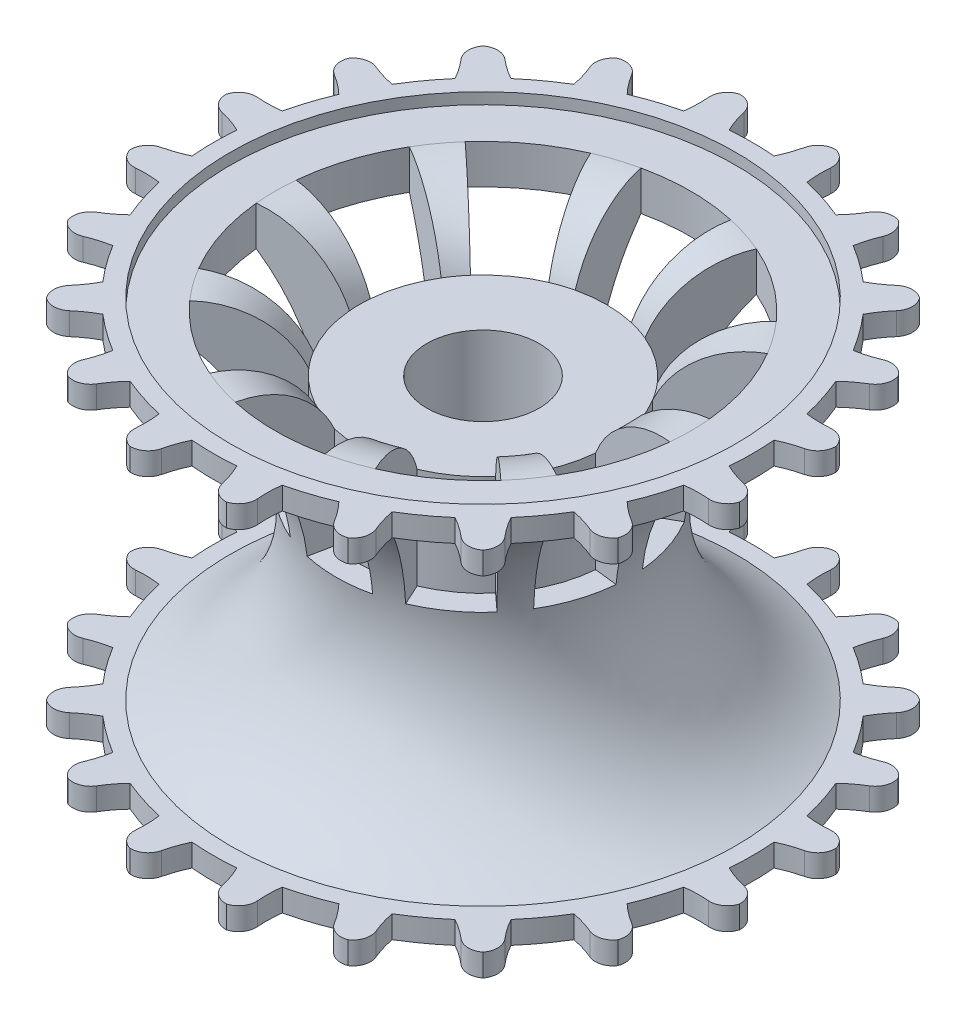
SolidWorks part; units mm, degrees
material "PE(聚乙烯)"
ref_plane "前视" through (0, 0, 0) normal (0, 0, 1) x (1, 0, 0)
ref_plane "上视" through (0, 0, 0) normal (0, 1, 0) x (1, 0, 0)
ref_plane "右视" through (0, 0, 0) normal (1, 0, 0) x (0, 0, -1)
sketch "草图1" plane through (0, 0, 0) normal (0, 0, 1) x (1, 0, 0)
  line L0 (0, 0) -> (0, -60) construction
  line L1 (5, 0) -> (11, 0)
  line L2 (22.5, 6) -> (27.5, 6)
  line L3 (27.5, 6) -> (27.5, 4)
  line L4 (27.5, 4) -> (22.5, 4)
  line L5 (5, 0) -> (5, -14)
  line L6 (5, -14) -> (2, -14)
  line L7 (2, -14) -> (2, -19)
  line L8 (22.5, 6) -> (22.5, 5)
  line L9 (22.5, 5) -> (18.5, 5)
  line L10 (22.5, -25) -> (27.5, -25)
  line L11 (27.5, -25) -> (27.5, -27)
  line L12 (27.5, -27) -> (22.5, -27)
  line L13 (12.5, -17) -> (10, -17)
  line L14 (10, -17) -> (10, -19)
  line L15 (10, -19) -> (6, -19)
  line L16 (6, -19) -> (6, -27)
  line L17 (6, -27) -> (4, -27)
  line L18 (2, -19) -> (4, -19)
  line L19 (4, -19) -> (4, -27)
  arc A0 (11, 0) -> (18.5, 5) centre (18.5, -3.125) cw
  arc A1 (22.5, 4) -> (22.5, -25) centre (28.8158, -10.5) ccw
  arc A2 (22.5, -27) -> (12.5, -17) centre (27.4359, -12.0641) cw
  dimension "D14" = 26
  dimension "D1" = 60
  dimension "D2" = 10
  dimension "D3" = 14
  dimension "D4" = 4
  dimension "D5" = 55
  dimension "D6" = 22
  dimension "D7" = 6
  dimension "D8" = 1
  dimension "D9" = 5
  dimension "D10" = 2
  dimension "D11" = 4
  dimension "D12" = 33
  dimension "D13" = 2
  dimension "D15" = 5
  dimension "D16" = 5
  dimension "D17" = 25
  dimension "D18" = 20
  dimension "D19" = 12
  dimension "D20" = 8
  dimension "D21" = 5
  dimension "D22" = 10
  dimension "D23" = 8
  dimension "D24" = 5
revolve "旋转1" add sketch "草图1" angle 360 about L0
sketch "草图2" plane through (0, 6, 0) normal (0, 1, 0) x (1, 0, 0)
  line L0 (-4, 18.0624) -> (-2.5, 10.7121)
  line L1 (0, 27.5) -> (0, -27.5) construction
  line L2 (2.5, 10.7121) -> (4, 18.0624)
  circle A0 centre (0, 0) radius 18.5 construction
  arc A1 (4, 18.0624) -> (-4, 18.0624) centre (0, 0) ccw
  circle A2 centre (0, 0) radius 11 construction
  arc A3 (2.5, 10.7121) -> (-2.5, 10.7121) centre (0, 0) ccw
  circle A4 centre (0, 0) radius 27.5 construction
  dimension "D1" = 8
  dimension "D2" = 5
extrude "切除-拉伸1" cut sketch "草图2" against normal blind 15
pattern_circular "阵列(圆周)1" count 10 over 360 about axis through (0, 0, 0) along (0, 1, 0) of "切除-拉伸1"
sketch "草图3" plane through (0, 6, 0) normal (0, 1, 0) x (1, 0, 0)
  line L0 (0, 27.5) -> (0, -27.5) construction
  arc A0 (2, 23.9165) -> (-2, 23.9165) centre (0, 0) ccw
  arc A1 (-2.708, 25.9327) -> (-2, 23.9165) centre (6.8709, 28.1642) ccw
  circle A2 centre (0, 0) radius 27.5 construction
  arc A3 (2.708, 25.9327) -> (2, 23.9165) centre (-6.8709, 28.1642) cw
  arc A4 (4.5, 27.1293) -> (-4.5, 27.1293) centre (0, 0) ccw
  arc A5 (-2.708, 25.9327) -> (-4.5, 27.1293) centre (-4.2422, 25.5753) ccw
  arc A6 (2.708, 25.9327) -> (4.5, 27.1293) centre (4.2422, 25.5753) cw
  dimension "D1" = 48
  dimension "D2" = 4
  dimension "D3" = 9
extrude "切除-拉伸2" cut sketch "草图3" against normal blind 60
pattern_circular "阵列(圆周)2" count 20 over 360 about axis through (0, 0, 0) along (0, 1, 0) of "切除-拉伸2"
sketch "草图4" plane through (0, -27, 0) normal (0, -1, 0) x (1, 0, 0)
  line L0 (-3, -2.6458) -> (3, -2.6458)
  circle A0 centre (0, 0) radius 4 construction
  arc A1 (-3, -2.6458) -> (3, -2.6458) centre (0, 0) ccw
  dimension "D1" = 6
extrude "凸台-拉伸1" add sketch "草图4" against normal blind 8 from offset 2
